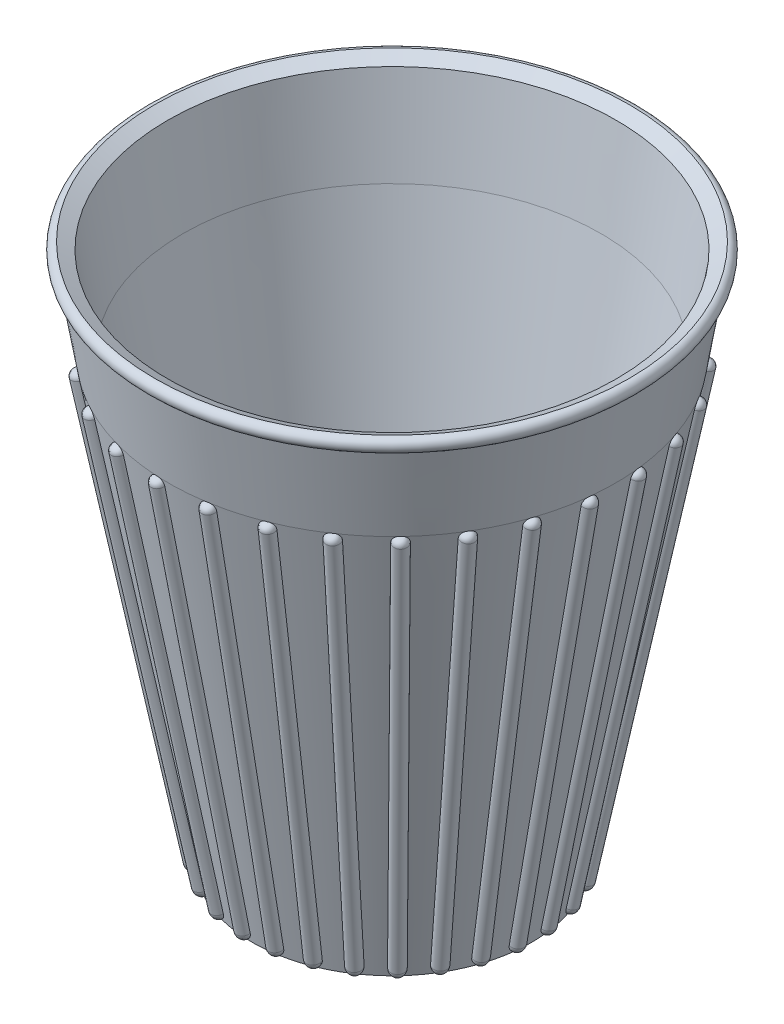
SolidWorks part; units mm, degrees
ref_plane "Front Plane" through (0, 0, 0) normal (0, 0, 1) x (1, 0, 0)
ref_plane "Top Plane" through (0, 0, 0) normal (0, 1, 0) x (1, 0, 0)
ref_plane "Right Plane" through (0, 0, 0) normal (1, 0, 0) x (0, 0, -1)
sketch "Sketch1" plane through (0, 0, 0) normal (0, 0, 1) x (1, 0, 0)
  line L0 (0, 0) -> (0, -77) construction
  line L1 (-20, -77) -> (20, -77) construction
  line L2 (-34, 0) -> (34, 0) construction
  line L3 (-32.1307, -1) -> (-34, 0)
  line L6 (21.5561, -64) -> (20, -77) construction
  line L7 (-12.6, -77) -> (-12.3226, -76.7781)
  line L9 (-34, -2) -> (34, -2) construction
  line L10 (-35, -1) -> (35, -1) construction
  line L11 (-32, -14) -> (32, -14) construction
  line L12 (-34, -2) -> (-32, -14)
  line L15 (34, -2) -> (32, -14) construction
  line L16 (32, -14) -> (27.5, -50.547) construction
  line L17 (27.5, -50.547) -> (23.9354, -64) construction
  line L19 (21.5561, -64) -> (23.9354, -64) construction
  line L22 (0, -74) -> (-18.5355, -74)
  line L27 (-29.964, -14) -> (-32.1307, -1)
  line L28 (-29.964, -14) -> (-18.5355, -74)
  line L29 (-20, -77) -> (-12.6, -77)
  line L30 (-12.6, -76.6) -> (-12.6, -75.2)
  line L31 (-12.6, -75.2) -> (0, -75.2)
  line L32 (0, -75.2) -> (0, -74)
  line L33 (-32, -14) -> (-20, -77)
  line L34 (-12.3851, -76.6) -> (-12.6, -76.6)
  arc A0 (-34, -2) -> (-34, 0) centre (-34, -1) cw
  arc A1 (34, -2) -> (34, 0) centre (34, -1) ccw construction
  arc A2 (-12.3226, -76.7781) -> (-12.3851, -76.6) centre (-12.3851, -76.7) ccw
  point P6 (0, -77)
  point P11 (0, 0)
  point P22 (0, -2)
  point P25 (0, -1)
  point P28 (0, -14)
  point P32 (-12.1, -76.6)
  dimension "D7" = 0.1
  dimension "D1" = 77
  dimension "D2" = 40
  dimension "D3" = 68
  dimension "D4" = 0.5
  dimension "D5" = 2
  dimension "D6" = 0.4
  dimension "D9" = 2
  dimension "D10" = 68
  dimension "D11" = 70
  dimension "D12" = 1
  dimension "D13" = 14
  dimension "D14" = 64
  dimension "D15" = 1.8
  dimension "D20" = 12.6
  dimension "D21" = 3
revolve "Revolve1" add sketch "Sketch1" angle 360 about L0
sketch "Sketch2" plane through (0, 0, 0) normal (0, 0, 1) x (1, 0, 0)
  line L1 (-32, -14) -> (-20, -77)
  line L4 (-32.9713, -8.9005) -> (9322.6341, -49125.8288) construction
  line L5 (-19.1725, -76) -> (-30.7915, -15) construction
  line L6 (-32, -14) -> (-20, -77) construction
  line L7 (-21.2085, -76) -> (-32.8275, -15)
  line L8 (-32, -14) -> (32, -14) construction
  line L11 (-20, -77) -> (-32, -14)
  line L12 (-20, -77) -> (20, -77) construction
  arc A3 (-32.8275, -15) -> (-32, -14) centre (-32, -14.8424) cw
  arc A4 (-21.2085, -76) -> (-20, -77) centre (-20, -75.7698) ccw
  dimension "D3" = 1
  dimension "D1" = 1
  dimension "D4" = 2
  dimension "D5" = 1
  dimension "D6" = 1
  dimension "D7" = 1
revolve "Revolve7" add sketch "Sketch2" angle 360 about L4
pattern_circular "CirPattern1" count 29 over 360 about axis through (0, -14, 0) along (0, 1, 0) of "Revolve7"
